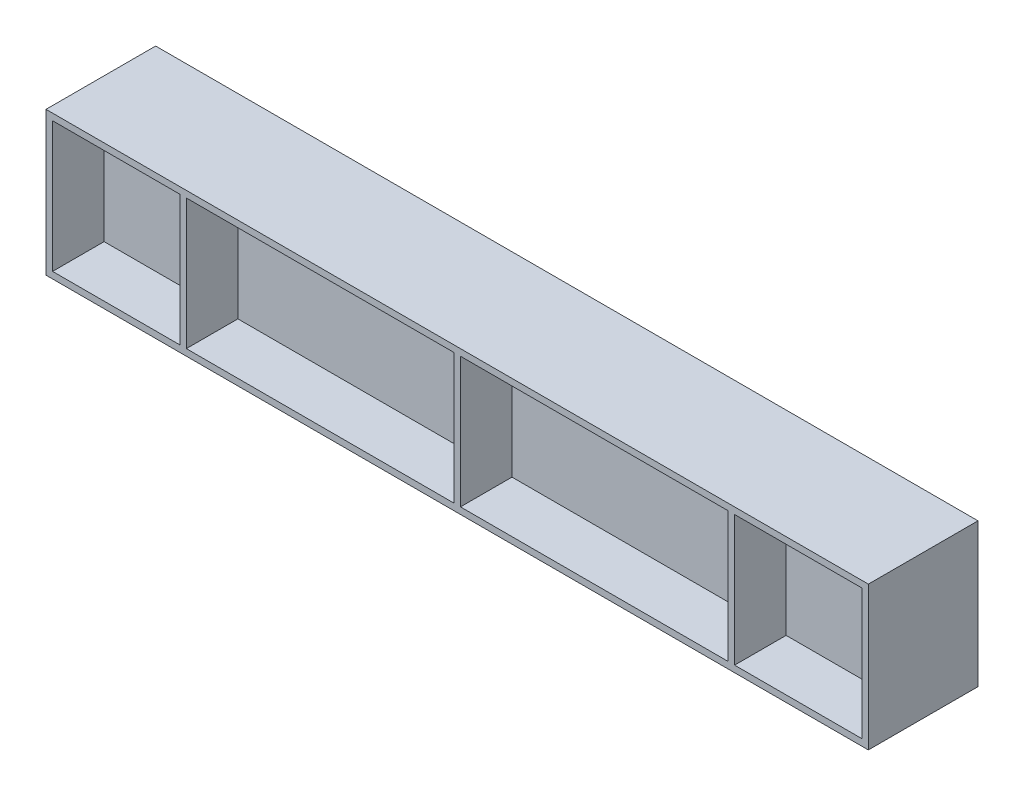
SolidWorks part; units mm, degrees
ref_plane "前视基准面" through (0, 0, 0) normal (0, 0, 1) x (1, 0, 0)
ref_plane "上视基准面" through (0, 0, 0) normal (0, 1, 0) x (1, 0, 0)
ref_plane "右视基准面" through (0, 0, 0) normal (1, 0, 0) x (0, 0, -1)
sketch "草图1" plane through (0, 0, 0) normal (0, 0, 1) x (1, 0, 0)
  line L1 (0, 0) -> (1500, 0)
  line L2 (0, 0) -> (0, 262)
  line L3 (0, 262) -> (1500, 262)
  line L4 (1500, 0) -> (1500, 262)
  dimension "D1" = 1500
  dimension "D2" = 262
extrude "拉伸1" add sketch "草图1" along normal blind 200
sketch "草图5" plane through (0, 0, 200) normal (0, 0, 1) x (1, 0, 0)
  line L0 (1500, 262) -> (0, 262) construction
  line L1 (12, 250) -> (244, 250)
  line L2 (12, 250) -> (12, 12)
  line L3 (12, 12) -> (244, 12)
  line L4 (244, 250) -> (244, 12)
  line L5 (0, 0) -> (1500, 0) construction
  line L6 (0, 262) -> (0, 0) construction
  line L8 (256, 250) -> (744, 250)
  line L9 (256, 250) -> (256, 12)
  line L10 (256, 12) -> (744, 12)
  line L11 (744, 250) -> (744, 12)
  line L12 (756, 250) -> (1244, 250)
  line L13 (756, 250) -> (756, 12)
  line L14 (756, 12) -> (1244, 12)
  line L15 (1244, 250) -> (1244, 12)
  line L32 (1256, 250) -> (1488, 250)
  line L33 (1256, 250) -> (1256, 12)
  line L34 (1256, 12) -> (1488, 12)
  line L35 (1488, 250) -> (1488, 12)
  dimension "D1" = 12
  dimension "D2" = 12
  dimension "D3" = 12
  dimension "D4" = 232
  dimension "D5" = 12
  dimension "D6" = 488
  dimension "D7" = 488
  dimension "D8" = 12
  dimension "D9" = 12
  dimension "D17" = 232
extrude "拉伸10" cut sketch "草图5" against normal through all
sketch "草图7" plane through (0, 0, 0) normal (0, -1, 0) x (1, 0, 0)
  line L0 (0, 100) -> (3607.9066, 100) construction
  line L1 (0, 200) -> (0, 0) construction
  line L2 (1500, 200) -> (1500, 0) construction
  line L3 (0, 106) -> (1500, 106)
  line L4 (0, 106) -> (0, 94)
  line L5 (0, 94) -> (1500, 94)
  line L6 (1500, 106) -> (1500, 94)
  dimension "D1" = 6
  dimension "D2" = 6
extrude "拉伸13" add sketch "草图7" against normal blind 260
